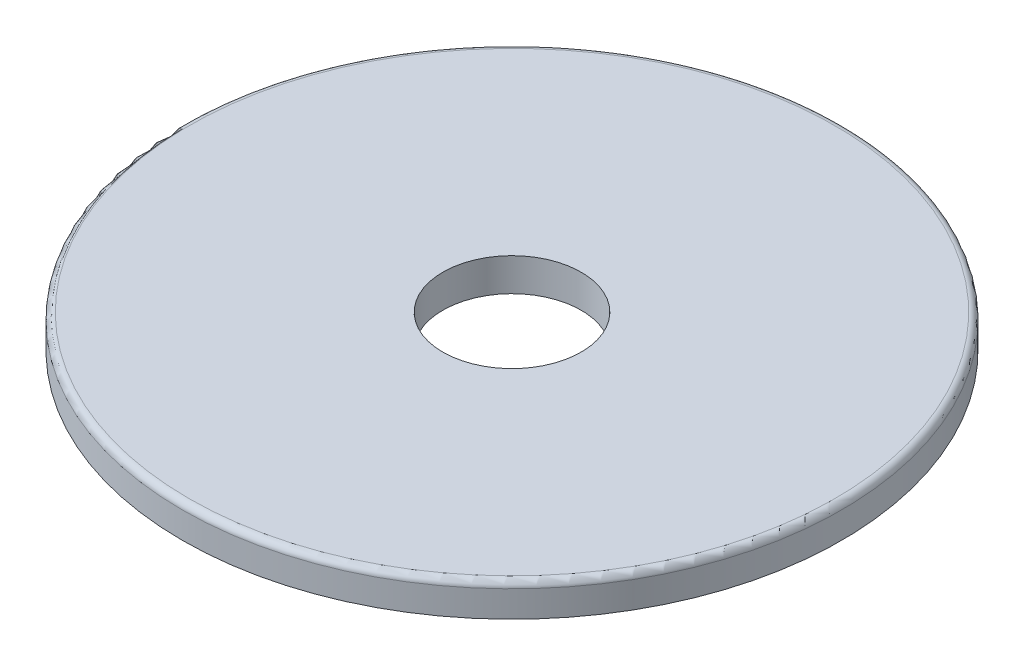
SolidWorks part; units mm, degrees
ref_plane "前视基准面" through (0, 0, 0) normal (0, 0, 1) x (1, 0, 0)
ref_plane "上视基准面" through (0, 0, 0) normal (0, 1, 0) x (1, 0, 0)
ref_plane "右视基准面" through (0, 0, 0) normal (1, 0, 0) x (0, 0, -1)
sketch "草图1" plane through (0, 0, 0) normal (0, 1, 0) x (1, 0, 0)
  circle A0 centre (0, 0) radius 10
  circle A1 centre (0, 0) radius 2.1
extrude "凸台-拉伸1" add sketch "草图1" along normal blind 1
fillet "圆角1" radius 0.2 1 edges at (0, 1, 10)
